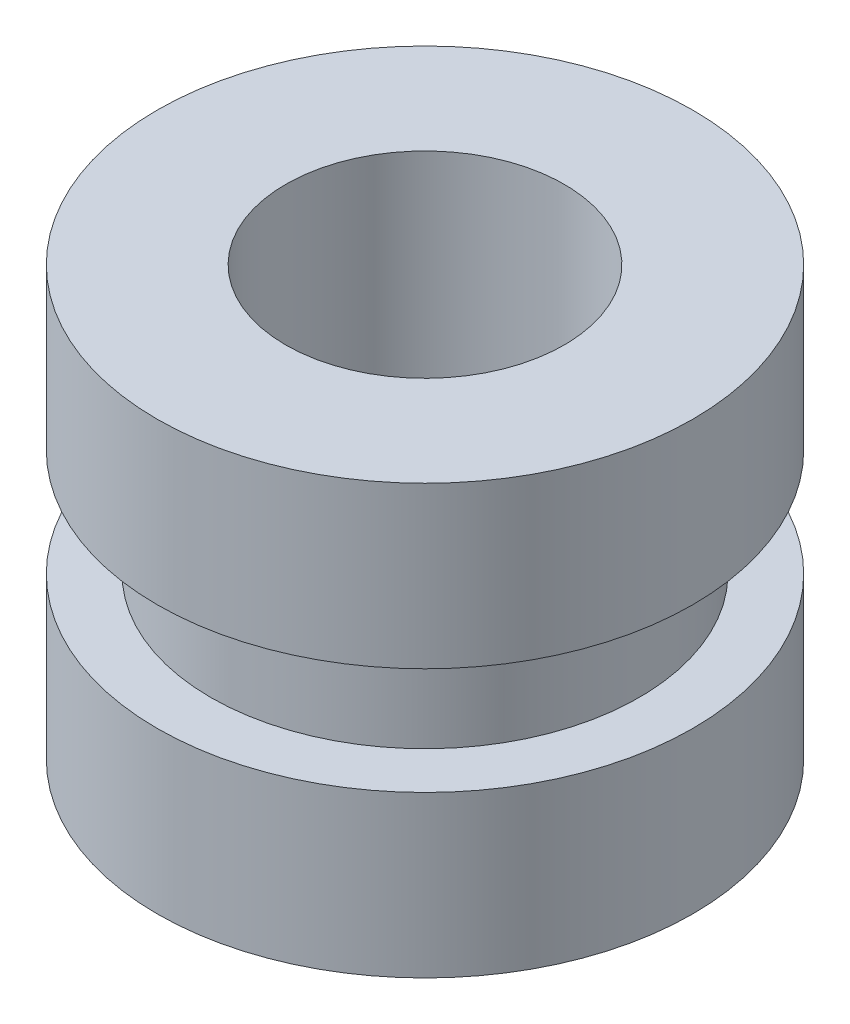
SolidWorks part; units mm, degrees
ref_plane "Front Plane" through (0, 0, 0) normal (0, 0, 1) x (1, 0, 0)
ref_plane "Top Plane" through (0, 0, 0) normal (0, 1, 0) x (1, 0, 0)
ref_plane "Right Plane" through (0, 0, 0) normal (1, 0, 0) x (0, 0, -1)
sketch "Sketch1" plane through (0, 0, 0) normal (0, 1, 0) x (1, 0, 0)
  circle A0 centre (0, 0) radius 1.3
  circle A1 centre (0, 0) radius 2
  dimension "D1" = 2.6
  dimension "D2" = 4
extrude "Boss-Extrude1" add sketch "Sketch1" along normal mid plane 1
sketch "Sketch2" plane through (0, 0.5, 0) normal (0, 1, 0) x (1, 0, 0)
  circle A0 centre (0, 0) radius 1.3 construction
  circle A1 centre (0, 0) radius 1.3
  circle A2 centre (0, 0) radius 2.5
  dimension "D1" = 5
extrude "Boss-Extrude2" add sketch "Sketch2" along normal blind 1.5
mirror "Mirror1" about plane through (0, 0, 0) normal (0, 1, 0) of "Boss-Extrude2"
